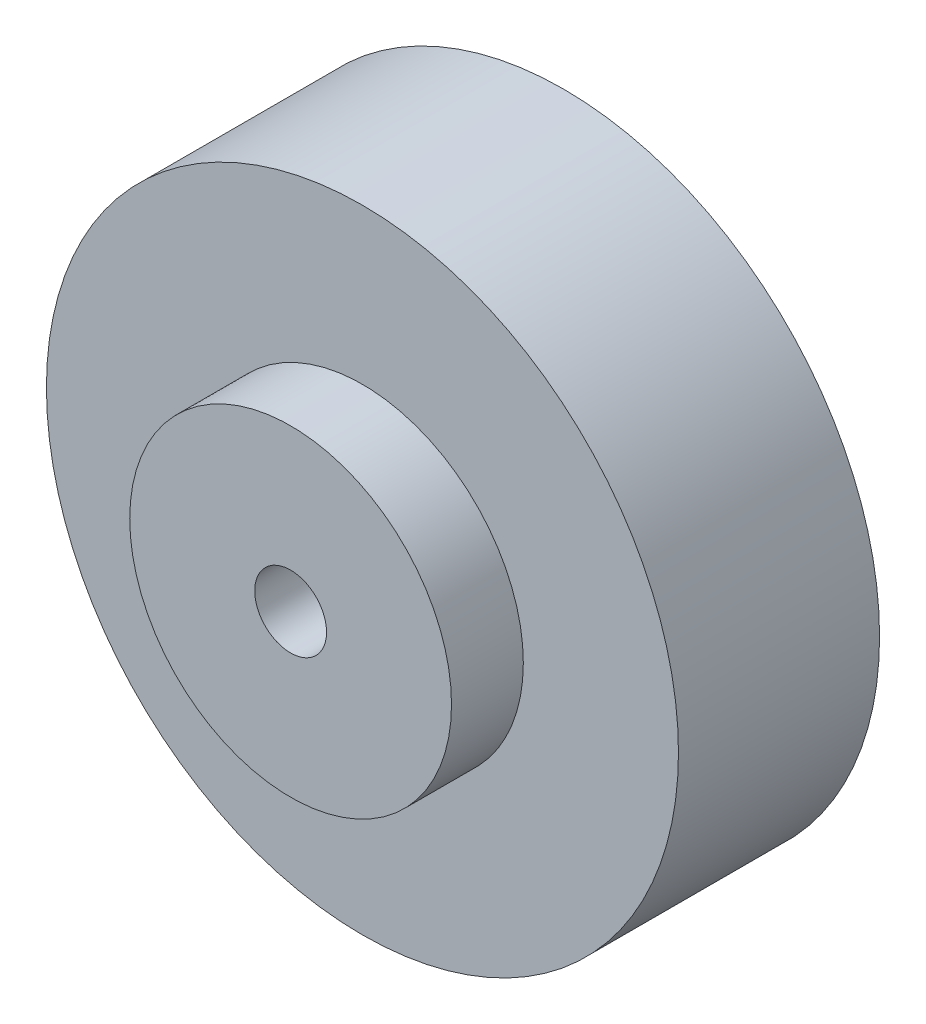
SolidWorks part; units mm, degrees
ref_plane "Front Plane" through (0, 0, 0) normal (0, 0, 1) x (1, 0, 0)
ref_plane "Top Plane" through (0, 0, 0) normal (0, 1, 0) x (1, 0, 0)
ref_plane "Right Plane" through (0, 0, 0) normal (1, 0, 0) x (0, 0, -1)
sketch "Sketch1" plane through (0, 0, 0) normal (0, 0, 1) x (1, 0, 0)
  circle A0 centre (0, 0) radius 34.925
  dimension "D1" = 69.85
extrude "Boss-Extrude1" add sketch "Sketch1" along normal blind 22.225
sketch "Sketch2" plane through (0, 0, 22.225) normal (0, 0, 1) x (1, 0, 0)
  circle A0 centre (0, 0) radius 17.78
  dimension "D1" = 35.56
extrude "Boss-Extrude2" add sketch "Sketch2" along normal blind 7.9375
sketch "Sketch3" plane through (0, 0, 30.1625) normal (0, 0, 1) x (1, 0, 0)
  circle A0 centre (0, 0) radius 3.9688
  dimension "D1" = 7.9375
extrude "Cut-Extrude1" cut sketch "Sketch3" against normal up to surface (30.1625 mm away) up to face at (34.925, 0, 0)
